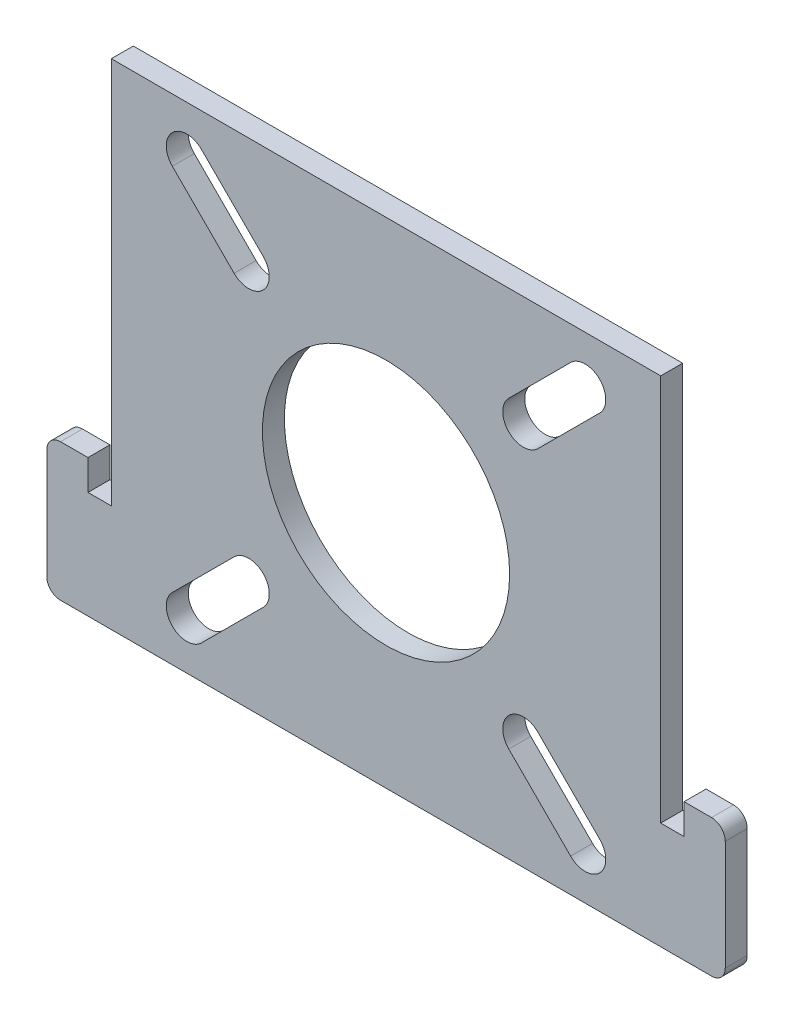
SolidWorks part; units mm, degrees
material "Thornel VCB-20 Carbon Cloth"
ref_plane "Front" through (0, 0, 0) normal (0, 0, 1) x (1, 0, 0)
ref_plane "Top" through (0, 0, 0) normal (0, 1, 0) x (1, 0, 0)
ref_plane "Right" through (0, 0, 0) normal (1, 0, 0) x (0, 0, -1)
sketch "Sketch1" plane through (0, 0, 0) normal (0, 0, 1) x (1, 0, 0)
  line L1 (-20, 18) -> (20, 18)
  line L2 (-20, 18) -> (-20, -18)
  line L3 (-20, -18) -> (20, -18)
  line L4 (20, 18) -> (20, -18)
  line L5 (-20, 18) -> (20, -18) construction
  line L6 (-20, -18) -> (20, 18) construction
  point P0 (0, 0)
  dimension "D1" = 40
  dimension "D2" = 36
extrude "Boss-Extrude1" add sketch "Sketch1" along normal blind 1.6
sketch "lense hole" plane through (0, 0, 0) normal (0, 0, 1) x (1, 0, 0)
  circle A0 centre (0, 0) radius 9
  dimension "D1" = 18
sketch "slot tracks" plane through (0, 0, 0) normal (0, 0, 1) x (1, 0, 0)
  line L1 (-10, 10) -> (10, 10)
  line L2 (-10, 10) -> (-10, -10)
  line L3 (-10, -10) -> (10, -10)
  line L4 (10, 10) -> (10, -10)
  line L5 (-10, 10) -> (10, -10) construction
  line L6 (-10, -10) -> (10, 10) construction
  line L7 (-14.5, 14.5) -> (14.5, 14.5)
  line L8 (-14.5, 14.5) -> (-14.5, -14.5)
  line L9 (-14.5, -14.5) -> (14.5, -14.5)
  line L10 (14.5, 14.5) -> (14.5, -14.5)
  line L11 (-14.5, 14.5) -> (14.5, -14.5) construction
  line L12 (-14.5, -14.5) -> (14.5, 14.5) construction
  point P0 (0, 0)
  point P6 (0, 0)
  dimension "D1" = 20
  dimension "D2" = 29
sketch "Sketch4" plane through (0, 0, 0) normal (0, 0, 1) x (1, 0, 0)
  line L0 (-14.5, 14.5) -> (-10, 10) construction
  line L1 (-13.4393, 15.5607) -> (-8.9393, 11.0607)
  line L2 (-15.5607, 13.4393) -> (-11.0607, 8.9393)
  line L3 (10, 10) -> (14.5, 14.5) construction
  line L4 (8.9393, 11.0607) -> (13.4393, 15.5607)
  line L5 (11.0607, 8.9393) -> (15.5607, 13.4393)
  line L6 (10, -10) -> (14.5, -14.5) construction
  line L7 (11.0607, -8.9393) -> (15.5607, -13.4393)
  line L8 (8.9393, -11.0607) -> (13.4393, -15.5607)
  line L9 (-14.5, -14.5) -> (-10, -10) construction
  line L10 (-15.5607, -13.4393) -> (-11.0607, -8.9393)
  line L11 (-13.4393, -15.5607) -> (-8.9393, -11.0607)
  arc A0 (-13.4393, 15.5607) -> (-15.5607, 13.4393) centre (-14.5, 14.5) ccw
  arc A1 (-11.0607, 8.9393) -> (-8.9393, 11.0607) centre (-10, 10) ccw
  arc A2 (8.9393, 11.0607) -> (11.0607, 8.9393) centre (10, 10) ccw
  arc A3 (15.5607, 13.4393) -> (13.4393, 15.5607) centre (14.5, 14.5) ccw
  arc A4 (11.0607, -8.9393) -> (8.9393, -11.0607) centre (10, -10) ccw
  arc A5 (13.4393, -15.5607) -> (15.5607, -13.4393) centre (14.5, -14.5) ccw
  arc A6 (-15.5607, -13.4393) -> (-13.4393, -15.5607) centre (-14.5, -14.5) ccw
  arc A7 (-8.9393, -11.0607) -> (-11.0607, -8.9393) centre (-10, -10) ccw
  point P4 (-12.25, 12.25)
  point P9 (12.25, 12.25)
  point P18 (12.25, -12.25)
  point P31 (-12.25, -12.25)
  dimension "D1" = 3
extrude "Cut-Extrude1" cut sketch "lense hole" along normal through all
extrude "Cut-Extrude2" cut sketch "Sketch4" along normal through all
sketch "Sketch5" plane through (0, 0, 0) normal (0, 0, 1) x (1, 0, 0)
  line L0 (20, -18) -> (24.7, -18)
  line L1 (24.7, -18) -> (24.7, -8)
  line L2 (24.7, -8) -> (21.7, -8)
  line L3 (21.7, -8) -> (21.7, -10.2)
  line L4 (21.7, -10.2) -> (20, -10.2)
  line L5 (20, -18) -> (20, 18) construction
  line L6 (20, -10.2) -> (20, -18)
  dimension "D1" = 7.8
  dimension "D2" = 3
  dimension "D3" = 1.7
  dimension "D4" = 10
extrude "Boss-Extrude2" add sketch "Sketch5" along normal up to surface (1.6 mm away) up to face at (12.25, -12.25, 1.6)
mirror "Mirror1" about plane through (0, 0, 0) normal (1, 0, 0) of "Boss-Extrude2"
fillet "Fillet1" radius 1 4 edges at (24.7, -8, 0.8) (24.7, -18, 0.8) (-24.7, -18, 0.8) (-24.7, -8, 0.8)
